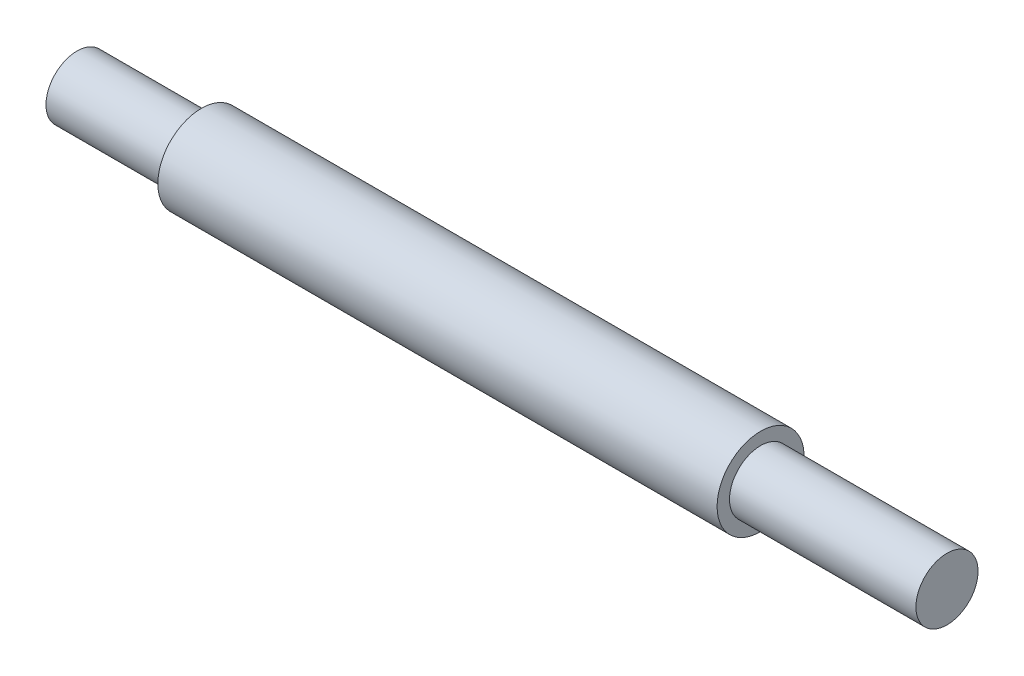
SolidWorks part; units mm, degrees
ref_plane "Front Plane" through (0, 0, 0) normal (0, 0, 1) x (1, 0, 0)
ref_plane "Top Plane" through (0, 0, 0) normal (0, 1, 0) x (1, 0, 0)
ref_plane "Right Plane" through (0, 0, 0) normal (1, 0, 0) x (0, 0, -1)
sketch "Sketch1" plane through (0, 0, 0) normal (0, 1, 0) x (1, 0, 0)
  line L0 (0, 0) -> (700, 0)
  line L1 (700, 0) -> (700, 25)
  line L2 (700, 25) -> (550, 25)
  line L3 (550, 25) -> (550, 35)
  line L4 (550, 35) -> (100, 35)
  line L5 (100, 35) -> (100, 25)
  line L6 (100, 25) -> (0, 25)
  line L7 (0, 25) -> (0, 0)
  dimension "D1" = 450
  dimension "D2" = 10
  dimension "D3" = 10
  dimension "D4" = 25
  dimension "D5" = 100
  dimension "D6" = 150
revolve "Revolve1" add sketch "Sketch1" angle 360 about L0
